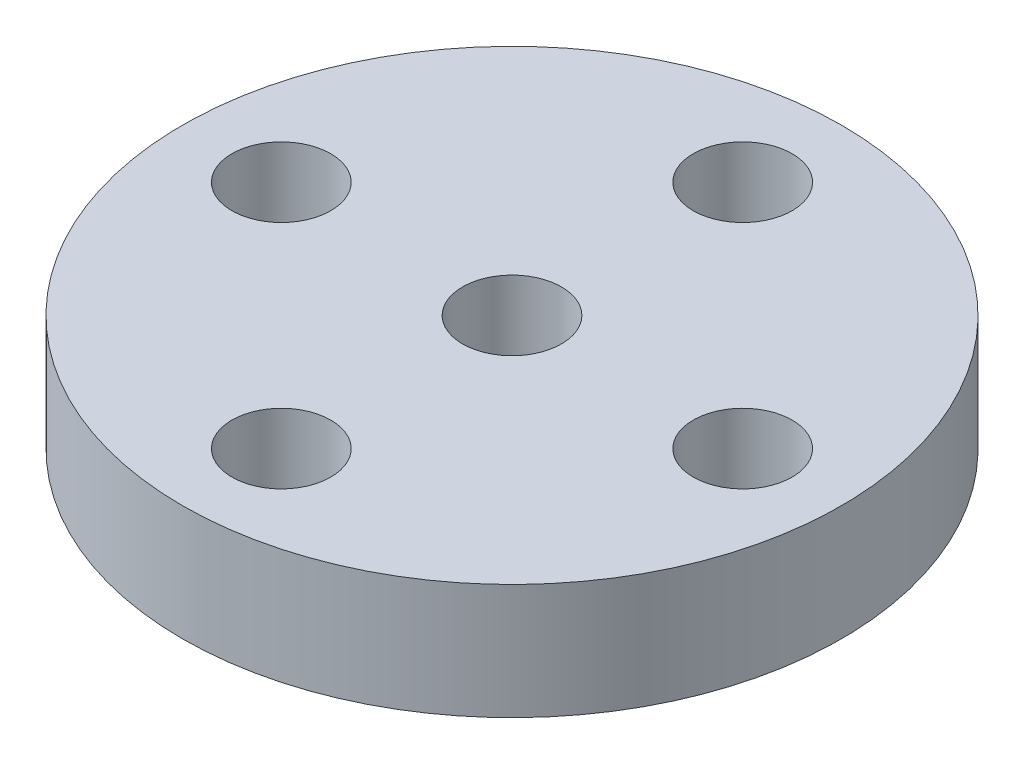
SolidWorks part; units mm, degrees
material "聚脂树脂"
ref_plane "前视基准面" through (0, 0, 0) normal (0, 0, 1) x (1, 0, 0)
ref_plane "上视基准面" through (0, 0, 0) normal (0, 1, 0) x (1, 0, 0)
ref_plane "右视基准面" through (0, 0, 0) normal (1, 0, 0) x (0, 0, -1)
other "Configuration Table"
sketch "草图1" plane through (0, 0, 0) normal (0, 1, 0) x (1, 0, 0)
  line L0 (0, 0) -> (0, 14.6276) construction
  line L1 (0, 0) -> (20.1674, 0) construction
  circle A0 centre (0, 0) radius 10
  circle A1 centre (0, 7) radius 1.5
  circle A2 centre (7, 0) radius 1.5
  circle A3 centre (0, 0) radius 1.5
  circle A4 centre (0, -7) radius 1.5
  circle A5 centre (-7, 0) radius 1.5
  dimension "D1" = 20
  dimension "D2" = 3
  dimension "D3" = 3
  dimension "D4" = 7
  dimension "D5" = 7
  dimension "D6" = 3
extrude "凸台-拉伸1" add sketch "草图1" along normal blind 3.5
